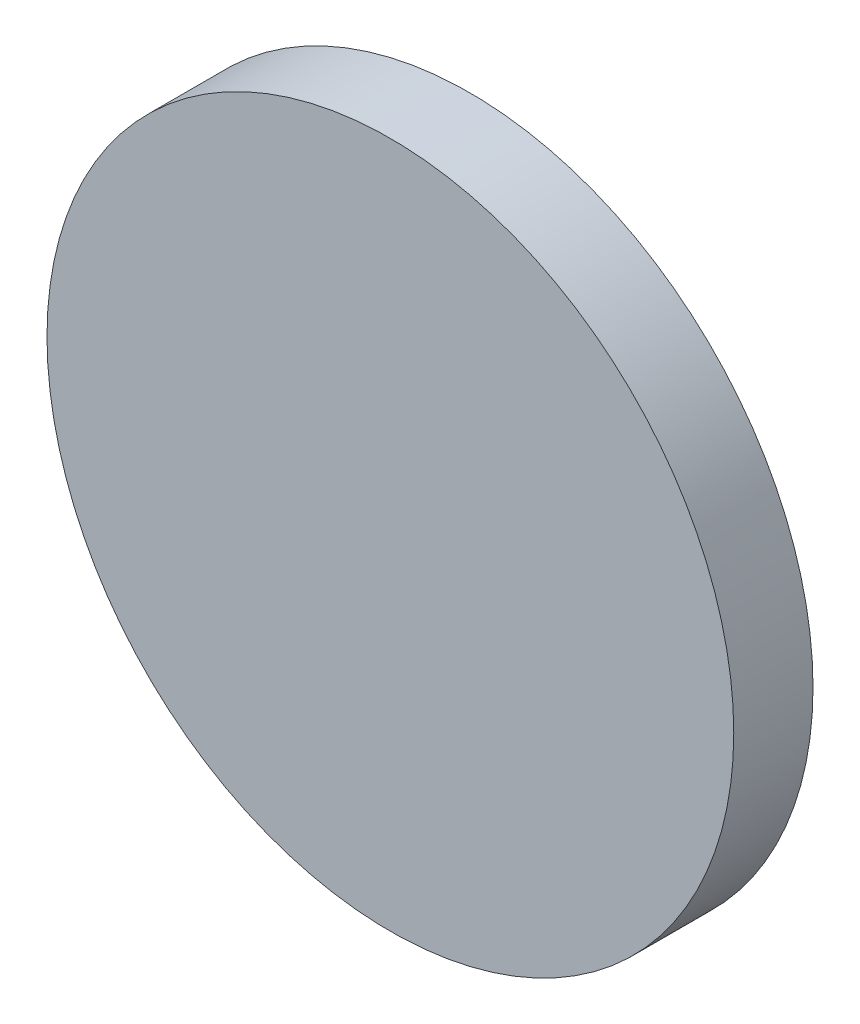
SolidWorks part; units mm, degrees
ref_plane "前视基准面" through (0, 0, 0) normal (0, 0, 1) x (1, 0, 0)
ref_plane "上视基准面" through (0, 0, 0) normal (0, 1, 0) x (1, 0, 0)
ref_plane "右视基准面" through (0, 0, 0) normal (1, 0, 0) x (0, 0, -1)
sketch "草图1" plane through (0, 0, 0) normal (0, 0, 1) x (1, 0, 0)
  circle A0 centre (0, 0) radius 13
extrude "凸台-拉伸1" add sketch "草图1" along normal blind 3
